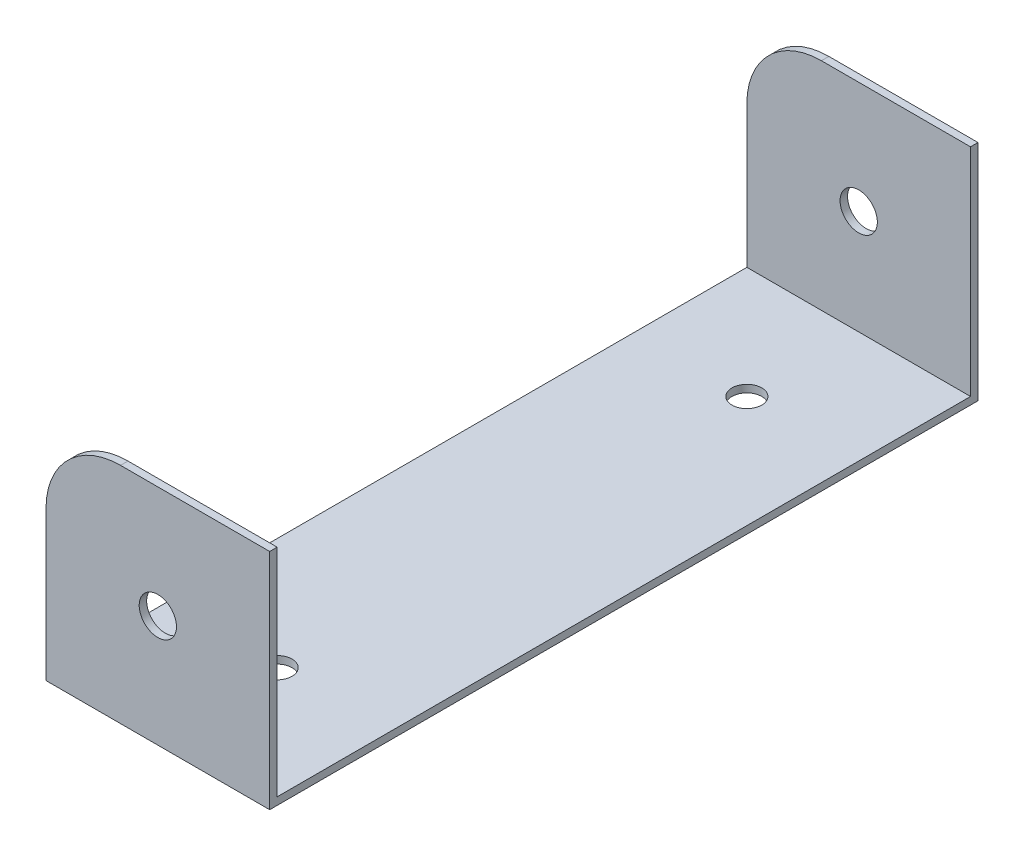
SolidWorks part; units mm, degrees
ref_plane "Alzado" through (0, 0, 0) normal (0, 0, 1) x (1, 0, 0)
ref_plane "Planta" through (0, 0, 0) normal (0, 1, 0) x (1, 0, 0)
ref_plane "Vista lateral" through (0, 0, 0) normal (1, 0, 0) x (0, 0, -1)
sketch "Croquis2" plane through (0, 0, 0) normal (0, 1, 0) x (1, 0, 0)
  line L1 (15, -47.5) -> (-15, -47.5)
  line L2 (15, -47.5) -> (15, 47.5)
  line L3 (15, 47.5) -> (-15, 47.5)
  line L4 (-15, -47.5) -> (-15, 47.5)
  line L5 (15, -47.5) -> (-15, 47.5) construction
  line L6 (15, 47.5) -> (-15, -47.5) construction
  point P0 (0, 0)
extrude "Saliente-Extruir1" add sketch "Croquis2" along normal blind 1
sketch "Croquis5" plane through (0, 0, 47.5) normal (0, 0, 1) x (1, 0, 0)
  line L0 (-15, 1) -> (-15, 30)
  line L1 (-15, 30) -> (15, 30)
  line L2 (15, 30) -> (15, 1)
  line L3 (15, 1) -> (-15, 1)
extrude "Saliente-Extruir2" add sketch "Croquis5" against normal blind 1
sketch "Croquis6" plane through (0, 0, -47.5) normal (0, 0, -1) x (-1, 0, 0)
  line L0 (-15, 1) -> (-15, 30)
  line L1 (-15, 1) -> (-15, 30) construction
  line L2 (-15, 30) -> (15, 30)
  line L3 (15, 30) -> (15, 1)
  line L4 (-15, 1) -> (15, 1) construction
  line L5 (15, 1) -> (-15, 1)
extrude "Saliente-Extruir3" add sketch "Croquis6" against normal blind 1
sketch "Croquis7" plane through (0, 0, -47.5) normal (0, 0, -1) x (-1, 0, 0)
  line L0 (0, 30) -> (0, 15) construction
  line L1 (15, 30) -> (-15, 30) construction
  circle A0 centre (0, 15) radius 2.5
extrude "Cortar-Extruir1" cut sketch "Croquis7" against normal blind 1
sketch "Croquis8" plane through (0, 0, 47.5) normal (0, 0, 1) x (1, 0, 0)
  line L0 (0, 30) -> (0, 15) construction
  line L1 (15, 30) -> (-15, 30) construction
  circle A0 centre (0, 15) radius 2.5
extrude "Cortar-Extruir2" cut sketch "Croquis8" against normal blind 1
fillet "Redondeo1" radius 10 2 edges at (-15, 30, -47) (-15, 30, 47)
sketch "Croquis9" plane through (0, 1, 0) normal (0, 1, 0) x (1, 0, 0)
  line L0 (0, 46.5) -> (0, 31.5) construction
  line L1 (15, 46.5) -> (-15, 46.5) construction
  line L2 (-15, 0) -> (15, 0) construction
  line L3 (-15, 46.5) -> (-15, -46.5) construction
  line L4 (15, -46.5) -> (15, 46.5) construction
  circle A0 centre (0, 31.5) radius 2
  circle A1 centre (0, -31.5) radius 2
extrude "Cortar-Extruir3" cut sketch "Croquis9" against normal blind 1
